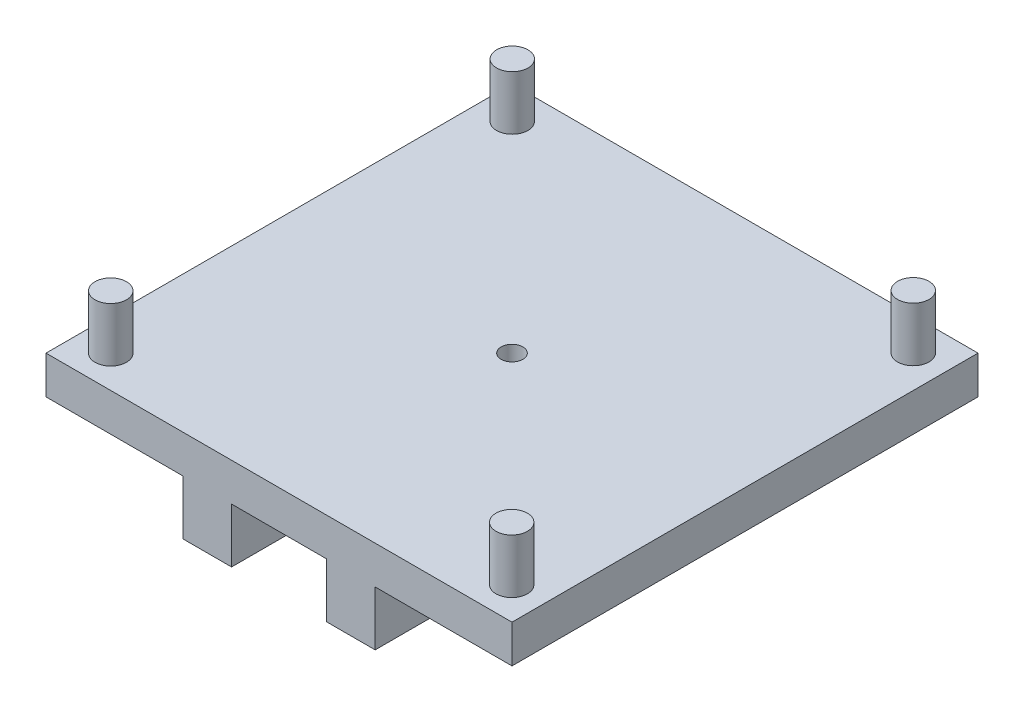
SolidWorks part; units mm, degrees
ref_plane "Front Plane" through (0, 0, 0) normal (0, 0, 1) x (1, 0, 0)
ref_plane "Top Plane" through (0, 0, 0) normal (0, 1, 0) x (1, 0, 0)
ref_plane "Right Plane" through (0, 0, 0) normal (1, 0, 0) x (0, 0, -1)
sketch "Sketch1" plane through (0, 0, 0) normal (0, 1, 0) x (1, 0, 0)
  line L1 (-21.5, -21.5) -> (21.5, -21.5)
  line L2 (-21.5, -21.5) -> (-21.5, 21.5)
  line L3 (-21.5, 21.5) -> (21.5, 21.5)
  line L4 (21.5, -21.5) -> (21.5, 21.5)
  line L5 (-21.5, -21.5) -> (21.5, 21.5) construction
  line L6 (-21.5, 21.5) -> (21.5, -21.5) construction
  circle A0 centre (0, 0) radius 1
  point P0 (0, 0)
  dimension "D1" = 43
  dimension "D2" = 43
extrude "Boss-Extrude1" add sketch "Sketch1" along normal blind 3.5
sketch "Sketch3" plane through (0, 3.5, 0) normal (0, 1, 0) x (1, 0, 0)
  line L0 (-21.5, 21.5) -> (-21.5, -21.5) construction
  line L3 (-21.5, 18.527) -> (-18.5, 18.527) construction
  line L4 (-18.5, 21.527) -> (-18.5, 18.527) construction
  circle A0 centre (-18.5, 18.527) radius 1.45
  dimension "D3" = 3
  dimension "D1" = 2.9
  dimension "D2" = 3
extrude "Boss-Extrude2" add sketch "Sketch3" along normal blind 5
mirror "Mirror2" about plane through (0, 0, 0) normal (0, 0, 1) of "Boss-Extrude2" second plane through (0, 0, 0) second plane normal (1, 0, 0)
sketch "Sketch4" plane through (0, 0, 0) normal (0, -1, 0) x (1, 0, 0)
  line L0 (-4.375, 0) -> (-4.375, 21.5) construction
  line L6 (-4.375, 0) -> (4.375, 0) construction
  line L7 (-21.5, 21.5) -> (21.5, 21.5) construction
  line L10 (-4.375, 21.5) -> (-8.875, 21.5)
  line L11 (-4.375, 21.5) -> (-4.375, -21.5)
  line L12 (-4.375, -21.5) -> (-8.875, -21.5)
  line L13 (-8.875, 21.5) -> (-8.875, -21.5)
  line L14 (21.5, -21.5) -> (-21.5, -21.5) construction
  point P0 (0, 0)
  point P4 (0, 0)
  dimension "D1" = 8.75
  dimension "D2" = 4.5
extrude "Boss-Extrude3" add sketch "Sketch4" along normal blind 5.03
mirror "Mirror3" about plane through (0, 0, 0) normal (1, 0, 0) of "Boss-Extrude3"
